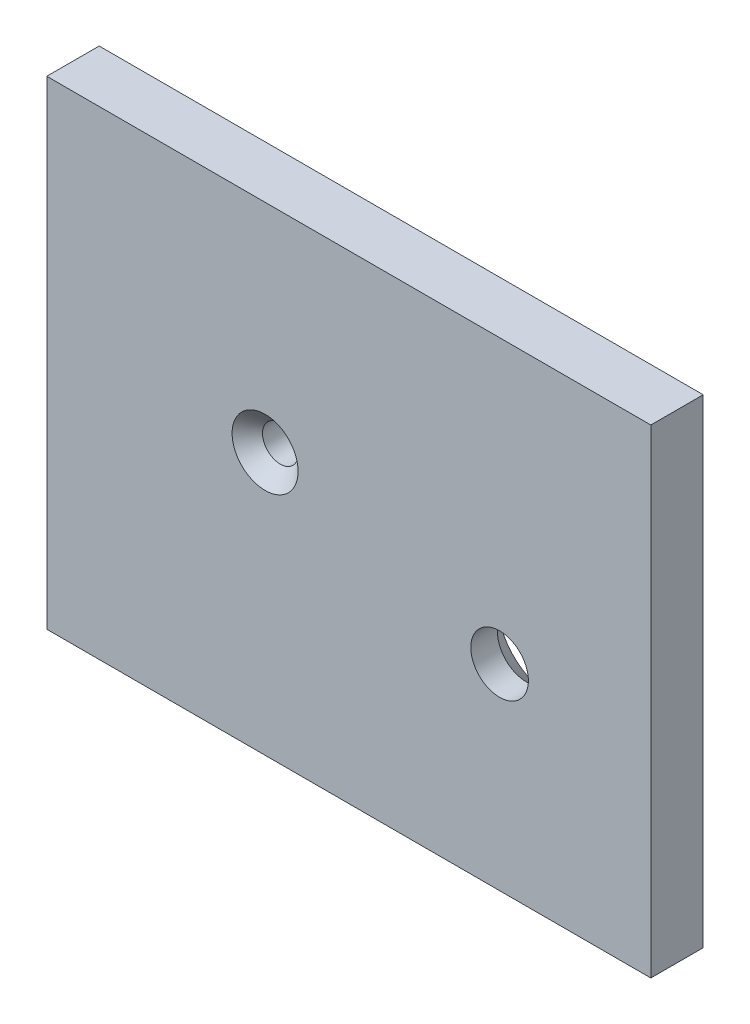
SolidWorks part; units mm, degrees
ref_plane "Front Plane" through (0, 0, 0) normal (0, 0, 1) x (1, 0, 0)
ref_plane "Top Plane" through (0, 0, 0) normal (0, 1, 0) x (1, 0, 0)
ref_plane "Right Plane" through (0, 0, 0) normal (1, 0, 0) x (0, 0, -1)
sketch "Sketch1" plane through (0, 0, 0) normal (0, 0, 1) x (1, 0, 0)
  line L0 (-57.6507, 0) -> (0, 0)
  line L1 (0, 0) -> (0, -45.7095)
  line L2 (-57.6507, 0) -> (-57.6507, -45.7095)
  line L3 (-57.6507, -45.7095) -> (0, -45.7095)
extrude "Boss-Extrude1" add sketch "Sketch1" along normal blind 5
sketch "Sketch11" plane through (0, 0, 5) normal (0, 0, 1) x (1, 0, 0)
  point P0 (-36.8151, -20.6674)
hole_wizard "CSK for M3 Countersunk Flat Head Screw2" positions "Sketch11" profile "Sketch10" countersink size "M3" standard "ISO" end condition through all
sketch "Sketch10" plane through (-36.8151, -20.6674, 5) normal (1, 0, 0) x (0, -1, 0)
  line L0 (0, 0) -> (0, 5)
  line L1 (0, 5) -> (1.7, 5)
  line L2 (1.7, 5) -> (1.7, 1.45)
  line L3 (1.7, 1.45) -> (3.15, 0)
  line L5 (3.15, 0) -> (0, 0)
  line L6 (-1.7, 1.45) -> (-3.15, 0) construction
  line L11 (0, -6.35) -> (0, 107.95) construction
  dimension "Thru Hole Dia." = 3.4
  dimension "Thru Hole Depth" = 5
  dimension "Near C'Sink Dia." = 6.3
  dimension "Near C'Sink Angle" = 90
sketch "Sketch14" plane through (0, 0, 0) normal (0, 0, -1) x (-1, 0, 0)
  point P0 (14.4347, -26.9762)
hole_wizard "CSK for M5 Countersunk Flat Head Screw1" positions "Sketch14" profile "Sketch13" countersink size "M5" standard "ISO" end condition through all
sketch "Sketch13" plane through (-14.4347, -26.9762, 0) normal (1, 0, 0) x (0, 1, 0)
  line L0 (0, 0) -> (0, 5)
  line L1 (0, 5) -> (2.75, 5)
  line L2 (2.75, 5) -> (2.75, 2.45)
  line L3 (2.75, 2.45) -> (5.2, 0)
  line L5 (5.2, 0) -> (0, 0)
  line L6 (-2.75, 2.45) -> (-5.2, 0) construction
  line L11 (0, -6.35) -> (0, 107.95) construction
  dimension "Thru Hole Dia." = 5.5
  dimension "Thru Hole Depth" = 5
  dimension "Near C'Sink Dia." = 10.4
  dimension "Near C'Sink Angle" = 90
